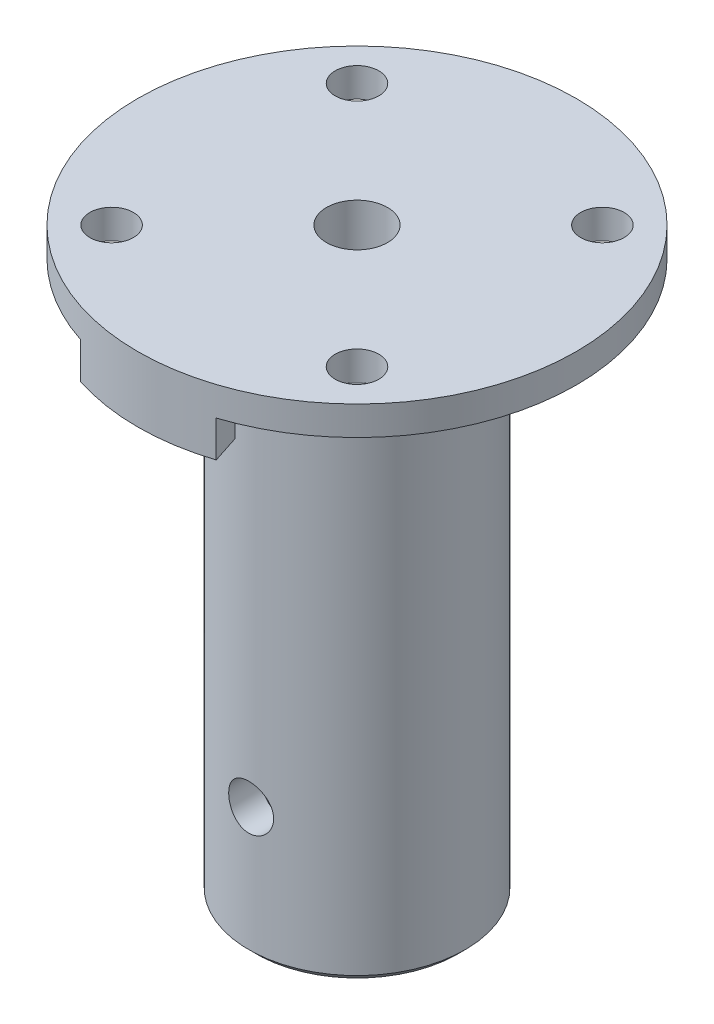
SolidWorks part; units mm, degrees
ref_plane "前视基准面" through (0, 0, 0) normal (0, 0, 1) x (1, 0, 0)
ref_plane "上视基准面" through (0, 0, 0) normal (0, 1, 0) x (1, 0, 0)
ref_plane "右视基准面" through (0, 0, 0) normal (1, 0, 0) x (0, 0, -1)
sketch "草图1" plane through (0, 0, 0) normal (0, 0, 1) x (1, 0, 0)
  line L0 (0, 0) -> (0, 12.42) construction
  line L1 (5.3, -24.9) -> (5.3, 15.1)
  line L2 (5.3, 15.1) -> (10.45, 15.1)
  line L3 (10.45, 15.1) -> (10.45, 10.1)
  line L4 (10.45, 10.1) -> (7.45, 10.1)
  line L5 (7.45, 10.1) -> (7.45, -24.9)
  line L6 (7.45, -24.9) -> (5.3, -24.9)
  point P8 (8.95, 10.1)
  dimension "D1" = 3
  dimension "D2" = 7.45
  dimension "D3" = 5.3
  dimension "D4" = 5
  dimension "D5" = 35
revolve "旋转1" add sketch "草图1" angle 360 about L0
sketch "草图2" plane through (0, 0, 0) normal (0, 0, 1) x (1, 0, 0)
  line L1 (-7.45, 10.1) -> (7.45, 10.1) construction
  circle A0 centre (0, -15.9) radius 1.55
  dimension "D1" = 26
  dimension "D2" = 3.1
extrude "切除-拉伸1" cut sketch "草图2" against normal through all both and the other way through all
chamfer "倒角1" distance 0.5 angle 45 1 edges at (0, -24.9, -7.45)
sketch "草图3" plane through (0, 0, 0) normal (1, 0, 0) x (0, 0, -1)
  line L0 (10.45, 15.1) -> (15.1, 15.1)
  line L1 (10.45, 15.1) -> (-10.45, 15.1) construction
  line L2 (15.1, 15.1) -> (15.1, 10.6)
  line L3 (15.1, 10.6) -> (13.1, 10.6)
  line L4 (13.1, 10.6) -> (13.1, 13.1)
  line L5 (13.1, 13.1) -> (10.4096, 13.1)
  line L6 (10.4096, 13.1) -> (10.4096, 15.1)
  line L7 (10.4096, 15.1) -> (10.45, 15.1)
  dimension "D1" = 4.5
  dimension "D2" = 2
  dimension "D3" = 15.1
  dimension "D4" = 2
revolve "旋转2" add sketch "草图3" angle 360 about axis through (0, 0, 0) along (0, -1, 0)
sketch "草图4" plane through (0, 15.1, 0) normal (0, 1, 0) x (1, 0, 0)
  circle A0 centre (0, 0) radius 2.1
  circle A1 centre (0, 0) radius 5.3 construction
  circle A2 centre (0, 0) radius 5.3
  dimension "D1" = 4.2
extrude "凸台-拉伸1" add sketch "草图4" against normal blind 3
sketch "草图5" plane through (0, 10.1, 0) normal (0, -1, 0) x (1, 0, 0)
  line L1 (-8.4499, 8.4499) -> (8.4499, 8.4499) construction
  line L2 (-8.4499, 8.4499) -> (-8.4499, -8.4499) construction
  line L3 (-8.4499, -8.4499) -> (8.4499, -8.4499) construction
  line L4 (8.4499, 8.4499) -> (8.4499, -8.4499) construction
  line L5 (-8.4499, 8.4499) -> (8.4499, -8.4499) construction
  line L6 (-8.4499, -8.4499) -> (8.4499, 8.4499) construction
  circle A0 centre (0, 0) radius 11.95 construction
  circle A1 centre (0, 0) radius 10.45 construction
  circle A2 centre (-8.4499, 8.4499) radius 1.5
  circle A3 centre (8.4499, 8.4499) radius 1.5
  circle A4 centre (8.4499, -8.4499) radius 1.5
  circle A5 centre (-8.4499, -8.4499) radius 1.5
  dimension "D1" = 1.5
  dimension "D3" = 3
  dimension "D4" = 3
  dimension "D5" = 3
  dimension "D6" = 3
  dimension "D2" = 90
extrude "切除-拉伸2" cut sketch "草图5" against normal blind 19
sketch "草图7" plane through (0, -24.9, 0) normal (0, -1, 0) x (1, 0, 0)
  line L0 (-3.2292, 9.9385) -> (-5.3259, 16.3914)
  line L1 (3.2292, 9.9385) -> (5.3259, 16.3914)
  line L3 (0, 5.0683) -> (0, 7.287) construction
  arc A1 (-3.2292, 9.9385) -> (3.2292, 9.9385) centre (0, 0) ccw
  arc A2 (-5.3259, 16.3914) -> (5.3259, 16.3914) centre (0, 0) ccw
  dimension "D1" = 36
  dimension "D2" = 18
extrude "切除-拉伸3" cut sketch "草图7" against normal blind 38
